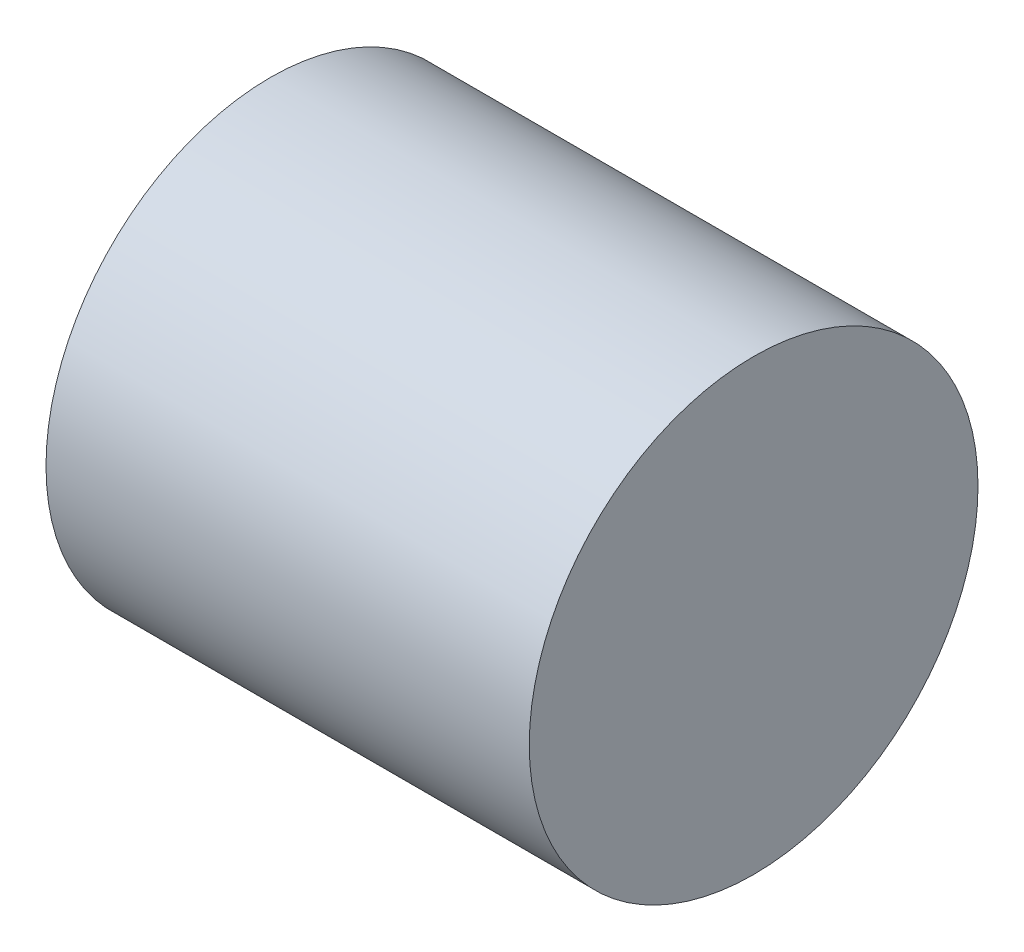
SolidWorks part; units mm, degrees
ref_plane "前视基准面" through (0, 0, 0) normal (0, 0, 1) x (1, 0, 0)
ref_plane "上视基准面" through (0, 0, 0) normal (0, 1, 0) x (1, 0, 0)
ref_plane "右视基准面" through (0, 0, 0) normal (1, 0, 0) x (0, 0, -1)
sketch "草图1" plane through (0, 0, 0) normal (1, 0, 0) x (0, 0, -1)
  circle A0 centre (0, 0) radius 3.25
  dimension "D1" = 6.5
extrude "凸台-拉伸1" add sketch "草图1" along normal blind 7
